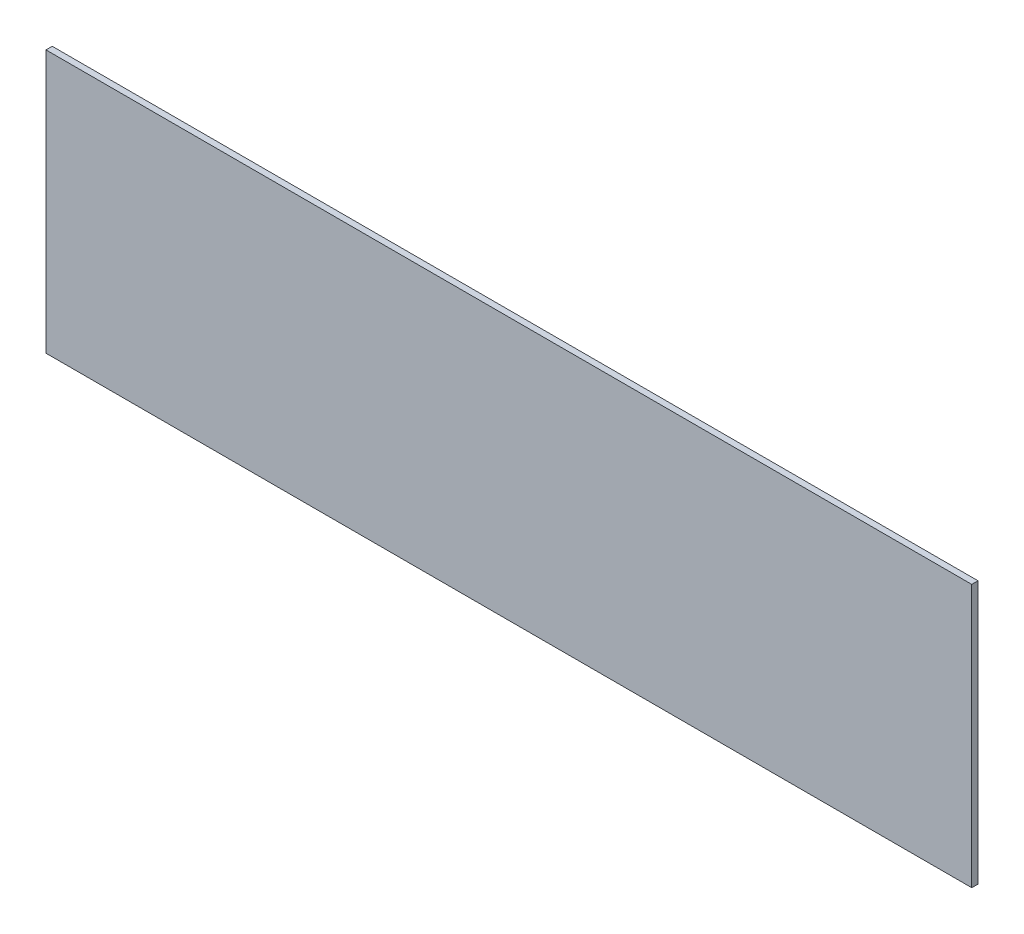
SolidWorks part; units mm, degrees
ref_plane "Front Plane" through (0, 0, 0) normal (0, 0, 1) x (1, 0, 0)
ref_plane "Top Plane" through (0, 0, 0) normal (0, 1, 0) x (1, 0, 0)
ref_plane "Right Plane" through (0, 0, 0) normal (1, 0, 0) x (0, 0, -1)
sketch "Sketch1" plane through (0, 0, 0) normal (0, 0, 1) x (1, 0, 0)
  line L1 (-234.95, -66.675) -> (234.95, -66.675)
  line L2 (-234.95, -66.675) -> (-234.95, 66.675)
  line L3 (-234.95, 66.675) -> (234.95, 66.675)
  line L4 (234.95, -66.675) -> (234.95, 66.675)
  line L5 (-234.95, -66.675) -> (234.95, 66.675) construction
  line L6 (-234.95, 66.675) -> (234.95, -66.675) construction
  point P0 (0, 0)
  dimension "D1" = 469.9
  dimension "D2" = 133.35
extrude "Boss-Extrude1" add sketch "Sketch1" along normal blind 3.175
